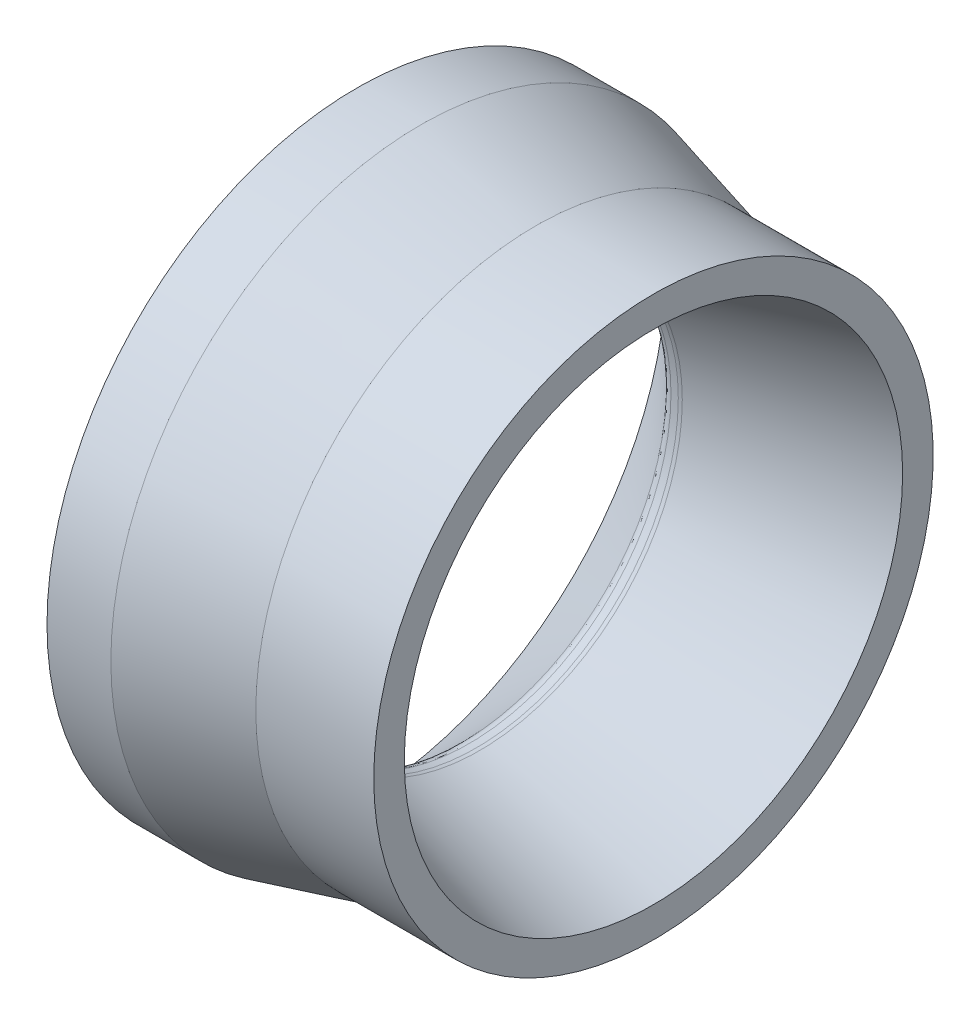
SolidWorks part; units mm, degrees
ref_plane "Front Plane" through (0, 0, 0) normal (0, 0, 1) x (1, 0, 0)
ref_plane "Top Plane" through (0, 0, 0) normal (0, 1, 0) x (1, 0, 0)
ref_plane "Right Plane" through (0, 0, 0) normal (1, 0, 0) x (0, 0, -1)
sketch "Sketch1" plane through (0, 0, 0) normal (0, 0, 1) x (1, 0, 0)
  line L0 (0, 0) -> (75.0218, 0) construction
  line L1 (0, 0) -> (0, 34.798) construction
  line L3 (12.0584, 22.7396) -> (19.7237, 15.0743)
  line L4 (20.2894, 14.84) -> (20.8263, 14.84)
  line L5 (21.0852, 14.8741) -> (33.8433, 18.2926)
  line L16 (12.0584, 22.7396) -> (16.7464, 22.7396)
  line L17 (16.7464, 22.7396) -> (25.1844, 20.535)
  line L18 (25.1844, 20.535) -> (33.8433, 20.535)
  line L19 (33.8433, 20.535) -> (33.8433, 18.2926)
  arc A0 (20.2894, 14.84) -> (19.7237, 15.0743) centre (20.2894, 15.64) cw
  arc A1 (21.0852, 14.8741) -> (20.8263, 14.84) centre (20.8263, 15.84) cw
  point P10 (19.958, 14.84)
  point P13 (20.958, 14.84)
  dimension "D6" = 0.8
  dimension "D7" = 1
  dimension "D1" = 34.798
  dimension "D2" = 45
  dimension "D3" = 14.84
  dimension "D4" = 1
  dimension "D5" = 15
revolve "Revolve1" add sketch "Sketch1" angle 360 about L0
